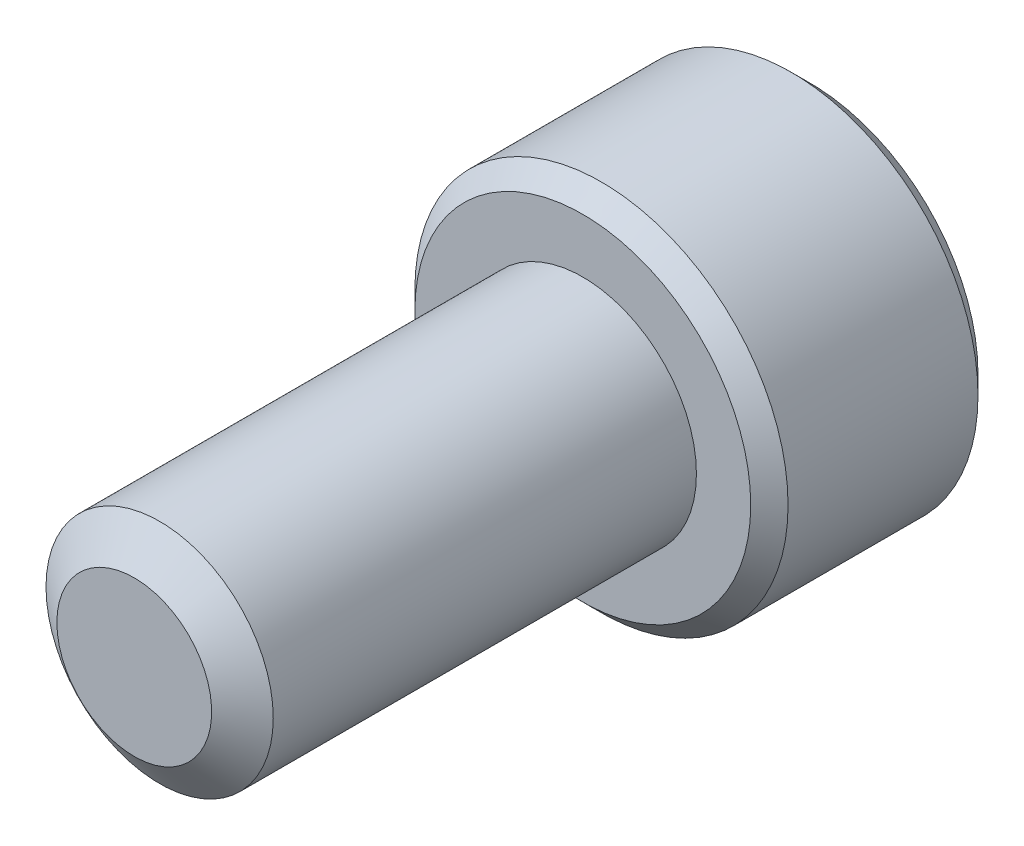
SolidWorks part; units mm, degrees
ref_plane "Front Plane" through (0, 0, 0) normal (0, 0, 1) x (1, 0, 0)
ref_plane "Top Plane" through (0, 0, 0) normal (0, 1, 0) x (1, 0, 0)
ref_plane "Right Plane" through (0, 0, 0) normal (1, 0, 0) x (0, 0, -1)
sketch "Sketch1" plane through (0, 0, 0) normal (0, 0, 1) x (1, 0, 0)
  circle A0 centre (0, 0) radius 2.413
  dimension "D1" = 4.826
extrude "Boss-Extrude1" add sketch "Sketch1" along normal blind 9.525
sketch "Sketch2" plane through (0, 0, 0) normal (1, 0, 0) x (0, 0, -1)
  line L0 (-9.525, 2.413) -> (-9.525, 1.6434)
  line L1 (-9.525, 2.413) -> (-9.525, -2.413) construction
  line L2 (-9.525, 1.6434) -> (-8.9862, 2.413)
  line L3 (0, 2.413) -> (-9.525, 2.413) construction
  line L4 (-8.9862, 2.413) -> (-9.525, 2.413)
  line L5 (0, 0) -> (-9.525, 0) construction
  dimension "D1" = 0.7696
  dimension "D2" = 55
revolve "Cut-Revolve1" cut sketch "Sketch2" angle 360 about L5
sketch "Sketch3" plane through (0, 0, 0) normal (0, 0, 1) x (1, 0, 0)
  circle A0 centre (0, 0) radius 3.9624
  dimension "D1" = 7.9248
extrude "Boss-Extrude2" add sketch "Sketch3" against normal blind 4.826
sketch "Sketch4" plane through (0, 0, 0) normal (0, 0, 1) x (1, 0, 0)
  line L1 (0, -2.2914) -> (1.9844, -1.1457)
  line L2 (1.9844, -1.1457) -> (1.9844, 1.1457)
  line L3 (1.9844, 1.1457) -> (0, 2.2914)
  line L4 (0, 2.2914) -> (-1.9844, 1.1457)
  line L5 (-1.9844, 1.1457) -> (-1.9844, -1.1457)
  line L6 (-1.9844, -1.1457) -> (0, -2.2914)
  circle A0 centre (0, 0) radius 1.9844 construction
  dimension "D1" = 3.9688
extrude "Cut-Extrude1" cut sketch "Sketch4" along normal blind 2.9766 from surface at -4.826 starting at face at (3.9624, 0, -4.826)
sketch "Sketch5" plane through (0, 0, -4.826) normal (0, 0, -1) x (-1, 0, 0)
  circle A0 centre (0, 0) radius 2.2914
extrude "Cut-Extrude2" cut sketch "Sketch5" against normal through all draft 45
chamfer "Chamfer1" distance 0.3962 angle 45 2 edges at (3.9624, 0, 0) (3.9624, 0, -4.826)
sketch "Sketch6" [suppressed] plane through (0, 0, 0) normal (1, 0, 0) x (0, 0, -1)
  line L0 (0, 2.413) -> (0, 5.2197)
  line L1 (0, 2.413) -> (-3.6076, 2.413)
  line L2 (0, 5.2197) -> (-0.1613, 5.2197)
  line L3 (-0.1613, 5.2197) -> (-3.2258, 2.5558)
  line L4 (0, 2.413) -> (-101.0612, 2.413) construction
  line L5 (0, 0) -> (-101.6, 0) construction
  line L6 (0, -2.413) -> (0, 2.413) construction
  line L7 (-101.6, 1.6434) -> (-101.6, -1.6434) construction
  arc A0 (-3.6076, 2.413) -> (-3.2258, 2.5558) centre (-3.6076, 2.995) ccw
  point P4 (0, 0)
  dimension "D1" = 5.2197
  dimension "D2" = 0.1613
  dimension "D3" = 3.2258
  dimension "D4" = 41
revolve "Revolve1" [suppressed] add sketch "Sketch6" angle 360 about L5
sketch "Sketch7" [suppressed] plane through (0, 0, 0) normal (0, 0, -1) x (-1, 0, 0)
  line L1 (-1.5875, -0.9165) -> (0, -1.8331)
  line L2 (0, -1.8331) -> (1.5875, -0.9165)
  line L3 (1.5875, -0.9165) -> (1.5875, 0.9165)
  line L4 (1.5875, 0.9165) -> (0, 1.8331)
  line L5 (0, 1.8331) -> (-1.5875, 0.9165)
  line L6 (-1.5875, 0.9165) -> (-1.5875, -0.9165)
  circle A0 centre (0, 0) radius 1.5875 construction
  dimension "D1" = 3.175
extrude "Cut-Extrude3" [suppressed] cut sketch "Sketch7" against normal blind 2.2581
sketch "Sketch8" [suppressed] plane through (0, 0, 0) normal (0, 0, -1) x (-1, 0, 0)
  circle A0 centre (0, 0) radius 1.8331
extrude "Cut-Extrude4" [suppressed] cut sketch "Sketch8" against normal through all draft 45
sketch "Sketch10" [suppressed] plane through (0, 0, 0) normal (1, 0, 0) x (0, 0, -1)
  line L0 (0, 0) -> (0, 4.5847)
  line L1 (0, 4.5847) -> (0.3629, 4.5847)
  line L2 (0, 0) -> (0.6227, 0)
  line L3 (0.6227, 0) -> (1.5392, 1.5875)
  line L4 (1.5392, 1.5875) -> (2.5654, 1.5875)
  line L5 (2.5654, 1.5875) -> (2.5654, 2.2225)
  line L6 (0, 0) -> (-4.1183, 0) construction
  arc A1 (0.3629, 4.5847) -> (2.5654, 2.2225) centre (-2.1862, 0) cw
  dimension "D1" = 0.3629
  dimension "D2" = 4.5847
  dimension "D3" = 0.6227
  dimension "D4" = 120
  dimension "D5" = 1.5875
  dimension "D6" = 2.2225
  dimension "D7" = 1.0262
revolve "Revolve2" [suppressed] add sketch "Sketch10" angle 360 about L6
sketch "Sketch11" [suppressed] plane through (0, 0, -2.5654) normal (0, 0, -1) x (-1, 0, 0)
  line L1 (-1.5875, -0.9165) -> (0, -1.8331)
  line L2 (0, -1.8331) -> (1.5875, -0.9165)
  line L3 (1.5875, -0.9165) -> (1.5875, 0.9165)
  line L4 (1.5875, 0.9165) -> (0, 1.8331)
  line L5 (0, 1.8331) -> (-1.5875, 0.9165)
  line L6 (-1.5875, 0.9165) -> (-1.5875, -0.9165)
  circle A0 centre (0, 0) radius 1.5875 construction
extrude "Cut-Extrude5" [suppressed] cut sketch "Sketch11" against normal up to vertex
sketch "Sketch12" [suppressed] plane through (0, 0, -2.5654) normal (0, 0, -1) x (-1, 0, 0)
  circle A0 centre (0, 0) radius 1.8331
extrude "Cut-Extrude6" [suppressed] cut sketch "Sketch12" against normal through all draft 45
sketch "Sketch13" [suppressed] plane through (0, 0, 0) normal (1, 0, 0) x (0, 0, -1)
  line L0 (0, 0) -> (0, 3.9624)
  line L1 (0, -2.413) -> (0, 2.413) construction
  line L2 (0, 3.9624) -> (1.924, 3.9624)
  line L3 (1.924, 3.9624) -> (2.3812, 3.5052)
  line L4 (2.3812, 3.5052) -> (2.3813, 0)
  line L5 (2.3813, 0) -> (0, 0)
  line L6 (0, 0) -> (-6.666, 0) construction
  dimension "D1" = 2.3813
  dimension "D2" = 3.9624
  dimension "D3" = 3.5052
  dimension "D4" = 1.924
revolve "Revolve3" [suppressed] add sketch "Sketch13" angle 360 about L6
sketch "Sketch14" [suppressed] plane through (0, 0, -2.3812) normal (0, 0, -1) x (-1, 0, 0)
  line L1 (0, -1.3748) -> (1.1906, -0.6874)
  line L2 (1.1906, -0.6874) -> (1.1906, 0.6874)
  line L3 (1.1906, 0.6874) -> (0, 1.3748)
  line L4 (0, 1.3748) -> (-1.1906, 0.6874)
  line L5 (-1.1906, 0.6874) -> (-1.1906, -0.6874)
  line L6 (-1.1906, -0.6874) -> (0, -1.3748)
  circle A0 centre (0, 0) radius 1.1906 construction
  dimension "D1" = 2.3813
extrude "Cut-Extrude7" [suppressed] cut sketch "Sketch14" against normal blind 1.8288
sketch "Sketch15" [suppressed] plane through (0, 0, -2.3812) normal (0, 0, -1) x (-1, 0, 0)
  circle A0 centre (0, 0) radius 1.3748
extrude "Cut-Extrude8" [suppressed] cut sketch "Sketch15" against normal through all draft 45
equation "\"Length\"= .375"
equation "\"D1@Boss-Extrude1\"=\"Length\""
